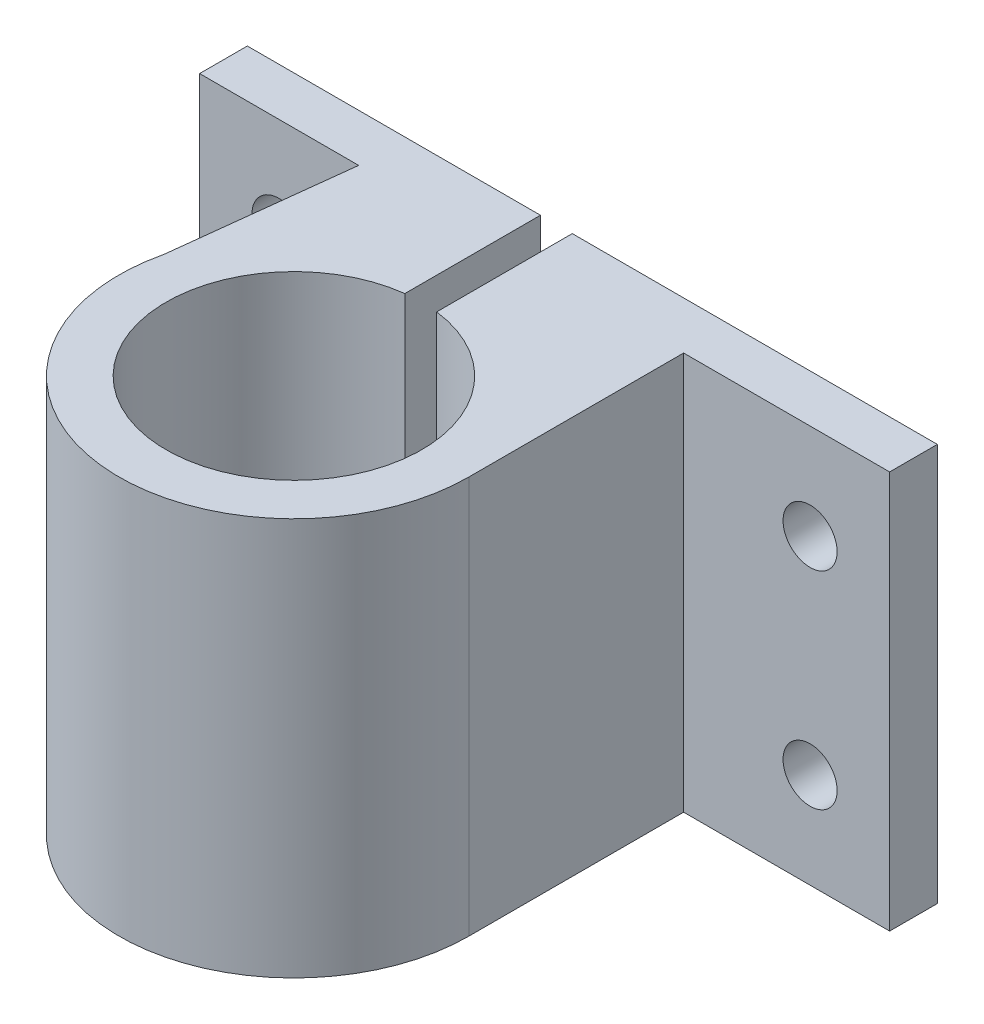
SolidWorks part; units mm, degrees
material "Custom Plastic"
ref_plane "Front Plane" through (0, 0, 0) normal (0, 0, 1) x (1, 0, 0)
ref_plane "Top Plane" through (0, 0, 0) normal (0, 1, 0) x (1, 0, 0)
ref_plane "Right Plane" through (0, 0, 0) normal (1, 0, 0) x (0, 0, -1)
sketch "Sketch3" plane through (0, 235.9236, 0) normal (0, 1, 0) x (1, 0, 0)
  line L0 (230.3238, 0) -> (233.7238, 0) construction
  line L2 (200.0181, -3) -> (200.0181, 0)
  line L3 (200.0181, 0) -> (226.1295, 0)
  line L4 (232.0238, 0) -> (237.0238, 0)
  line L5 (-40.7762, 0) -> (264.0238, 0) construction
  line L6 (237.0238, 0) -> (237.0238, -3)
  line L7 (237.0238, -3) -> (226.1295, -3)
  line L13 (200.0181, -33) -> (226.1295, 0) construction
  line L14 (200.0181, 0) -> (226.1295, -33) construction
  line L15 (230.3238, 0) -> (233.7238, 0)
  line L16 (237.0238, 0) -> (226.1295, 0)
  line L17 (200.0181, 0) -> (190.0181, 0)
  line L18 (226.1295, -3) -> (224.0738, -3)
  line L19 (190.0181, 0) -> (200.0181, 0)
  line L22 (200.0181, 0) -> (200.0181, -3)
  line L23 (237.0238, -3) -> (226.1295, -3)
  line L24 (237.0238, -3) -> (237.0238, 0)
  line L25 (237.0238, 0) -> (226.1295, 0)
  line L27 (224.0738, -16.5) -> (224.0738, 0)
  line L28 (214.0738, -27.5) -> (212.4071, -27.5)
  line L29 (237.0238, 0) -> (224.0738, 0)
  line L32 (214.0738, 0) -> (212.0738, 0)
  line L34 (214.0738, -33) -> (212.0738, 0) construction
  line L35 (214.0738, 0) -> (212.0738, -33) construction
  line L36 (214.0738, -8.5242) -> (214.0738, 0)
  line L37 (212.0738, -8.5242) -> (212.0738, 0)
  line L38 (202.0738, -16.5) -> (203.9958, 0)
  line L39 (200.0181, -3) -> (203.6463, -3)
  line L40 (203.6463, 0) -> (204.0313, 0)
  line L41 (203.6463, -3) -> (193.6463, -3)
  line L42 (203.6463, -3) -> (203.6463, 0)
  line L43 (203.6463, 0) -> (193.6463, 0)
  line L44 (193.6463, -3) -> (193.6463, 0)
  arc A0 (212.0738, -5.5455) -> (214.0738, -5.5455) centre (213.0738, -16.5) ccw
  circle A1 centre (213.0738, -16.5) radius 8.0383 construction
  arc A3 (212.0738, -8.5242) -> (214.0738, -8.5242) centre (213.0738, -16.5) ccw
extrude "Boss-Extrude1" add sketch "Sketch3" against normal up to surface (25 mm away)
sketch "Sketch4" plane through (0, 0, 3) normal (0, 0, 1) x (1, 0, 0)
  line L0 (198.6375, 210.7466) -> (198.6375, 236.4903)
  line L1 (232.0238, 216.9236) -> (-49767.9762, 216.9236) construction
  line L2 (231.9362, 229.9236) -> (-49768.0638, 229.9236) construction
  line L4 (193.6463, 210.9236) -> (203.6463, 210.9236)
  line L5 (203.6463, 210.9236) -> (203.6463, 235.9236)
  line L6 (203.6463, 235.9236) -> (193.6463, 235.9236)
  line L7 (193.6463, 235.9236) -> (193.6463, 210.9236)
  line L8 (193.6463, 210.9236) -> (203.6463, 210.9236)
  line L9 (203.6463, 210.9236) -> (203.6463, 235.9236)
  line L10 (203.6463, 235.9236) -> (193.6463, 235.9236)
  line L11 (193.6463, 235.9236) -> (193.6463, 210.9236)
  circle A0 centre (232.0238, 216.9236) radius 1.7 construction
  circle A1 centre (232.0238, 229.9236) radius 1.7 construction
  circle A2 centre (232.0238, 216.9236) radius 1.7
  circle A3 centre (232.0238, 229.9236) radius 1.7
  circle A6 centre (198.6375, 216.9236) radius 1.7
  circle A7 centre (198.6375, 229.9236) radius 1.7
  dimension "D1" = 0
extrude "Cut-Extrude1" cut sketch "Sketch4" against normal blind 10 contours L0 A7 | L0 A7 | L0 A6 | L0 A6 | A3 | A2
